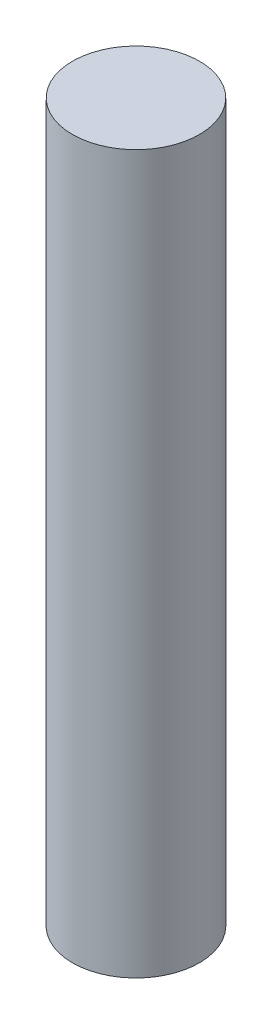
SolidWorks part; units mm, degrees
ref_plane "Alzado" through (0, 0, 0) normal (0, 0, 1) x (1, 0, 0)
ref_plane "Planta" through (0, 0, 0) normal (0, 1, 0) x (1, 0, 0)
ref_plane "Vista lateral" through (0, 0, 0) normal (1, 0, 0) x (0, 0, -1)
sketch "Croquis1" plane through (0, 0, 0) normal (0, 1, 0) x (1, 0, 0)
  circle A0 centre (0, 0) radius 2.475
  dimension "D1" = 4.95
extrude "Saliente-Extruir1" add sketch "Croquis1" along normal blind 27.96
